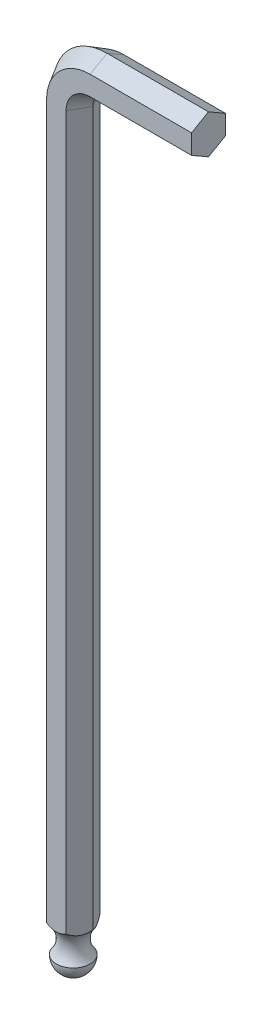
SolidWorks part; units mm, degrees
ref_plane "Vorne" through (0, 0, 0) normal (0, 0, 1) x (1, 0, 0)
ref_plane "Oben" through (0, 0, 0) normal (0, 1, 0) x (1, 0, 0)
ref_plane "Rechts" through (0, 0, 0) normal (1, 0, 0) x (0, 0, -1)
sketch "Skizze1" plane through (0, 0, 0) normal (0, 0, 1) x (1, 0, 0)
  line L0 (0, 0) -> (0, 220)
  line L1 (10, 230) -> (40, 230)
  arc A0 (0, 220) -> (10, 230) centre (10, 220) cw
  point P6 (0, 230)
  dimension "D3" = 10
  dimension "D1" = 230
  dimension "D2" = 40
sketch "Skizze3" plane through (0, 0, 0) normal (0, 1, 0) x (1, 0, 0)
  line L0 (-5.7735, 0) -> (5.7735, 0) construction
  line L1 (-2.8868, 5) -> (-5.7735, 0)
  line L2 (-5.7735, 0) -> (-2.8868, -5)
  line L3 (-2.8868, -5) -> (2.8868, -5)
  line L4 (2.8868, -5) -> (5.7735, 0)
  line L5 (5.7735, 0) -> (2.8868, 5)
  line L6 (2.8868, 5) -> (-2.8868, 5)
  circle A0 centre (0, 0) radius 5 construction
  dimension "D1" = 10
sweep "Austragung4" add profiles "Skizze3" path "Skizze1"
sketch "Skizze6" plane through (0, 0, 0) normal (1, 0, 0) x (0, 0, -1)
  line L0 (0, 7.8104) -> (0, -7.0578) construction
  line L1 (-5, 220) -> (-5, 0) construction
  line L2 (0, -5) -> (0, 5)
  arc A0 (0, -5) -> (0, 5) centre (0, 0) ccw
revolve "Rotation5" add sketch "Skizze6" angle 360 about L0
sketch "Skizze8" plane through (0, 0, 0) normal (0, 0, 1) x (1, 0, 0)
  line L0 (0, 0) -> (0, 50.305) construction
  line L1 (-5.7735, -0.9) -> (-5.1096, -0.1232)
  line L2 (-5.7735, 220) -> (-5.7735, 0) construction
  line L3 (-5.7735, 4.1) -> (5.7735, 4.1) construction
  line L5 (-5.1096, 8.3232) -> (-5.7735, 9.1)
  line L6 (-5.7735, 9.1) -> (-5.7735, -0.9)
  line L7 (5.7735, 220) -> (5.7735, 0) construction
  arc A0 (-5.1096, -0.1232) -> (-5.1096, 8.3232) centre (-10.0507, 4.1) ccw
  point P14 (-1.5, 4.1)
  dimension "D1" = 10
  dimension "D4" = 6.5
  dimension "D2" = 4.1
  dimension "D3" = 1.5
revolve "Schnitt-Rotation1" cut sketch "Skizze8" angle 360 about L0
